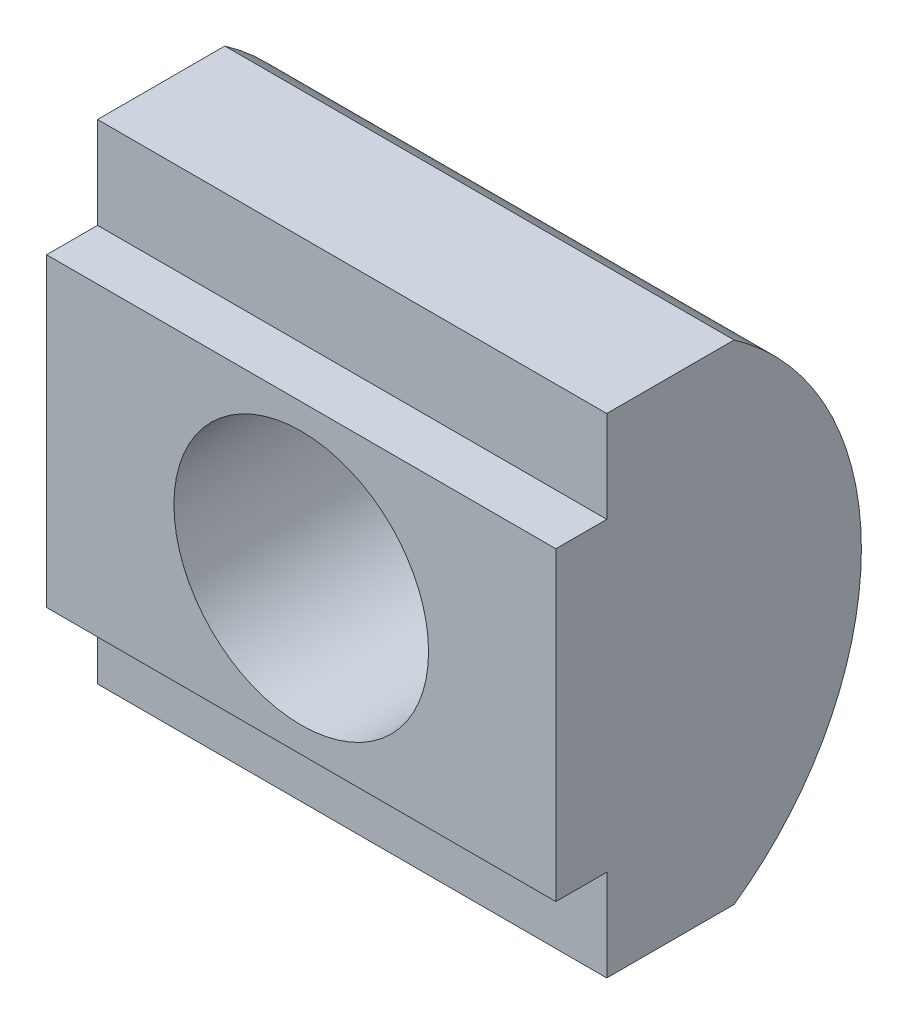
SolidWorks part; units mm, degrees
ref_plane "前视基准面" through (0, 0, 0) normal (0, 0, 1) x (1, 0, 0)
ref_plane "上视基准面" through (0, 0, 0) normal (0, 1, 0) x (1, 0, 0)
ref_plane "右视基准面" through (0, 0, 0) normal (1, 0, 0) x (0, 0, -1)
sketch "草图1" plane through (0, 0, 0) normal (0, 0, 1) x (1, 0, 0)
  line L1 (-5, 3) -> (5, 3)
  line L2 (-5, 3) -> (-5, -3)
  line L3 (-5, -3) -> (5, -3)
  line L4 (5, 3) -> (5, -3)
  circle A0 centre (0, 0) radius 2.5
  dimension "D5" = 5
  dimension "D1" = 6
  dimension "D2" = 10
  dimension "D3" = 3
  dimension "D4" = 5
extrude "凸台-拉伸1" add sketch "草图1" along normal blind 6
cosmetic thread "装饰螺纹线1" parameters "D1"=5, "D2"=6
sketch "草图2" plane through (0, 0, 0) normal (0, 0, 1) x (1, 0, 0)
  line L0 (-5, -4.8) -> (-5, 4.8)
  line L1 (-5, 4.8) -> (5, 4.8)
  line L2 (5, 4.8) -> (5, -4.8)
  line L3 (5, -4.8) -> (-5, -4.8)
  line L4 (-5, -4.8) -> (-5.593, -4.8)
  line L5 (-5, 3) -> (-5, -3) construction
  circle A0 centre (0, 0) radius 2.5 construction
  circle A1 centre (0, 0) radius 2.5
  dimension "D1" = 10
  dimension "D2" = 9.6
  dimension "D3" = 4.8
extrude "凸台-拉伸2" add sketch "草图2" along normal blind 5 contours L3 L2 L1 L0 A1
sketch "草图3" plane through (5, 0, 0) normal (1, 0, 0) x (0, 0, -1)
  line L0 (-6, 0) -> (0, 0) construction
  line L1 (-6, -3) -> (-6, 3) construction
  line L2 (-5, 4.8) -> (0, 4.8) construction
  line L3 (-5, -4.8) -> (0, -4.8) construction
  line L4 (-2.5, 4.8) -> (0, 4.8)
  line L5 (0, 4.8) -> (0, -4.8)
  line L6 (0, -4.8) -> (-2.5, -4.8)
  arc A0 (-2.5, 4.8) -> (-2.5, -4.8) centre (-5.858, 0) cw
  line M3 (-5, -4.8) -> (0, -4.8)
  line M4 (0, -4.8) -> (0, 4.8)
  line M5 (0, 4.8) -> (-5, 4.8)
extrude "切除-拉伸1" cut sketch "草图3" against normal blind 15 contours A0 L5 M5 | A0 M4 M3
